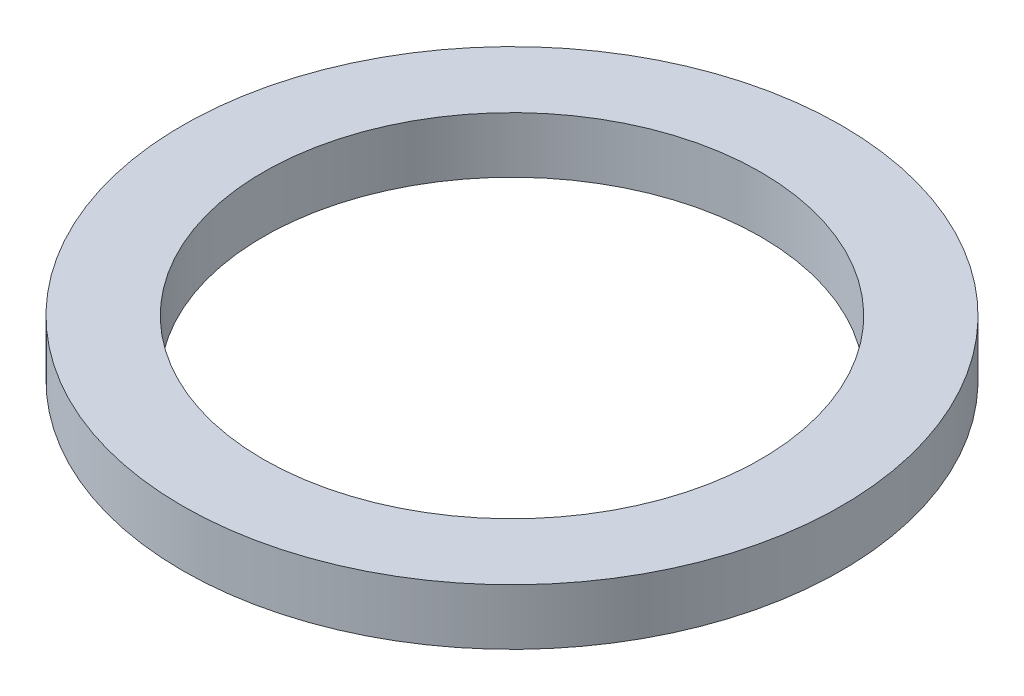
SolidWorks part; units mm, degrees
material "Copper"
ref_plane "Front Plane" through (0, 0, 0) normal (0, 0, 1) x (1, 0, 0)
ref_plane "Top Plane" through (0, 0, 0) normal (0, 1, 0) x (1, 0, 0)
ref_plane "Right Plane" through (0, 0, 0) normal (1, 0, 0) x (0, 0, -1)
sketch "Sketch1" plane through (0, 0, 0) normal (0, 1, 0) x (1, 0, 0)
  circle A0 centre (0, 0) radius 5.3
  circle A1 centre (0, 0) radius 4
  dimension "D1" = 8
  dimension "D2" = 10.6
extrude "Boss-Extrude1" add sketch "Sketch1" along normal mid plane 0.9
